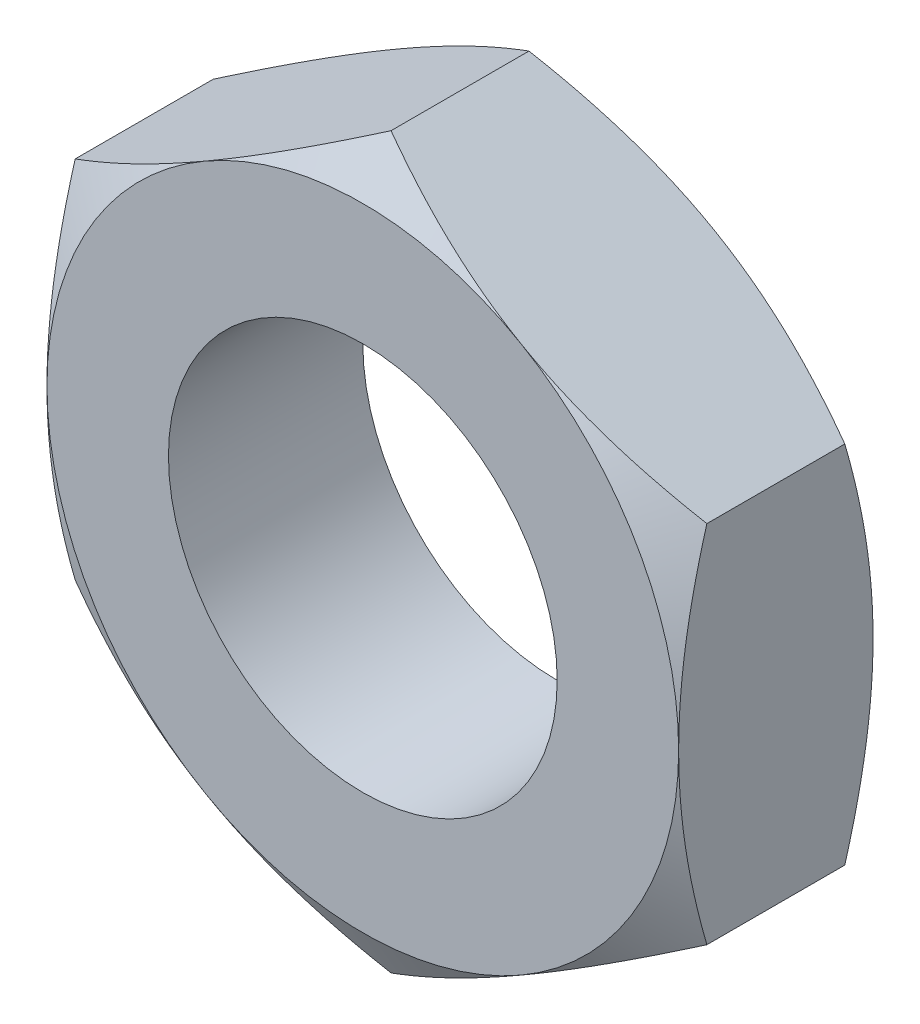
SolidWorks part; units mm, degrees
material "1.4000 (X6Cr13)"
ref_plane "Płaszczyzna przednia" through (0, 0, 0) normal (0, 0, 1) x (1, 0, 0)
ref_plane "Płaszczyzna górna" through (0, 0, 0) normal (0, 1, 0) x (1, 0, 0)
ref_plane "Płaszczyzna prawa" through (0, 0, 0) normal (1, 0, 0) x (0, 0, -1)
sketch "Szkic1" plane through (0, 0, 0) normal (0, 0, 1) x (1, 0, 0)
  line L1 (-6.5, 3.7528) -> (-6.5, -3.7528)
  line L2 (-6.5, -3.7528) -> (0, -7.5056)
  line L3 (0, -7.5056) -> (6.5, -3.7528)
  line L4 (6.5, -3.7528) -> (6.5, 3.7528)
  line L5 (6.5, 3.7528) -> (0, 7.5056)
  line L6 (0, 7.5056) -> (-6.5, 3.7528)
  circle A0 centre (0, 0) radius 4
  circle A1 centre (0, 0) radius 6.5 construction
  dimension "d" = 8
  dimension "s" = 13
extrude "Dodanie-wyciągnięcie1" add sketch "Szkic1" along normal mid plane 4
sketch "Szkic2" plane through (0, 0, 2) normal (0, 0, 1) x (1, 0, 0)
  circle A0 centre (0, 0) radius 6.5
  dimension "D1" = 13
extrude "Wytnij-wyciągnięcie2" cut sketch "Szkic2" against normal blind 4 draft 60 flip side to cut
mirror "Lustro1" about plane through (0, 0, 0) normal (0, 0, 1) of "Wytnij-wyciągnięcie2"
equation "\"D1@Szkic2\" = \"s@Szkic1\""
equation "\"D1@Wytnij-wyciągnięcie2\" = \"m@Dodanie-wyciągnięcie1\""
